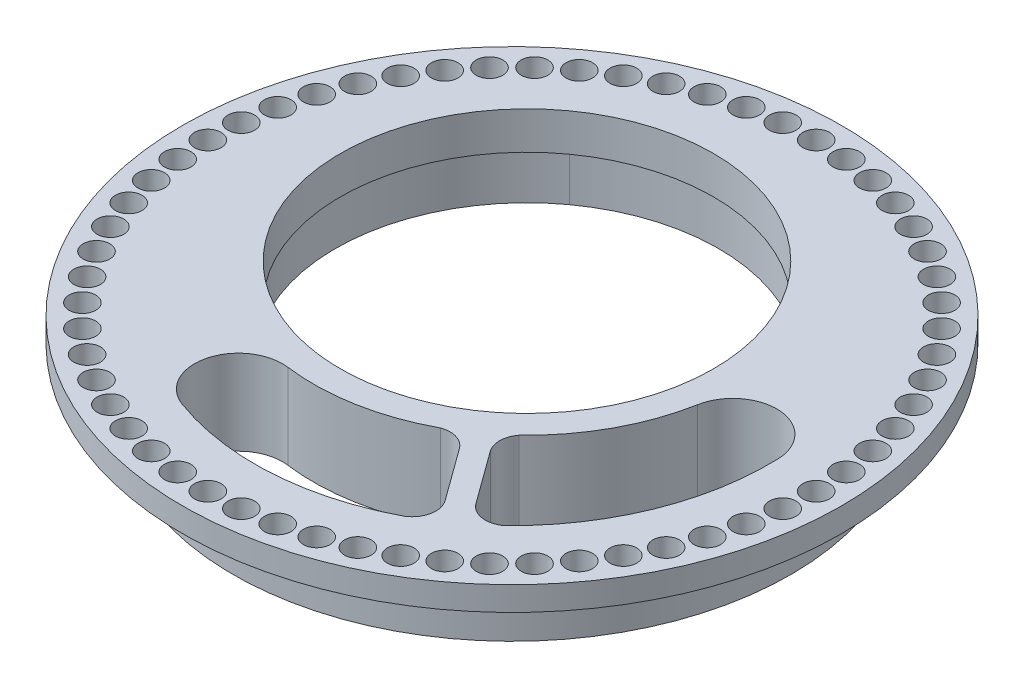
SolidWorks part; units mm, degrees
material "7075-T6, Plate (SS)"
ref_plane "X-Y Datum" through (0, 0, 0) normal (0, 0, 1) x (1, 0, 0)
ref_plane "X-Z Datum" through (0, 0, 0) normal (0, 1, 0) x (1, 0, 0)
ref_plane "Y-Z Datum" through (0, 0, 0) normal (1, 0, 0) x (0, 0, -1)
sketch "Sketch1" plane through (0, 0, 0) normal (0, 1, 0) x (1, 0, 0)
  line L0 (0, 0) -> (0, -12.7) construction
  line L1 (0, -43.0151) -> (0, 43.0151) construction
  line L2 (0, 61.9125) -> (0, 52.3875)
  circle A0 centre (0, -12.7) radius 35.052
  circle A1 centre (0, 0) radius 52.3875 construction
  circle A2 centre (0, 0) radius 57.15 construction
  circle A3 centre (0, 0) radius 61.9125
  point P12 (0, 57.15)
  dimension "D2" = 70.104
  dimension "D3" = 104.775
  dimension "D4" = 123.825
  dimension "D5" = 114.3
  dimension "D1" = 12.7
extrude "Boss-Extrude1" add sketch "Sketch1" along normal blind 4.5212
sketch "Sketch3" plane through (0, 4.5212, 0) normal (0, 1, 0) x (1, 0, 0)
  circle A0 centre (0, 0) radius 52.3875 construction
  circle A1 centre (0, 0) radius 52.3875
extrude "Boss-Extrude2" add sketch "Sketch3" along normal blind 11.43
sketch "Sketch4" plane through (0, 0, 0) normal (0, -1, 0) x (1, 0, 0)
  circle A0 centre (0, 12.7) radius 35.052 construction
  circle A1 centre (0, 12.7) radius 35.052
extrude "Cut-Extrude1" cut sketch "Sketch4" against normal through all
sketch "Sketch9" plane through (0, 15.9512, 0) normal (0, 1, 0) x (1, 0, 0)
  circle A0 centre (0, -12.7) radius 35.052 construction
  circle A1 centre (0, -12.7) radius 35.052 construction
  circle A2 centre (0, -12.7) radius 36
  dimension "D1" = 72
extrude "Cut-Extrude3" cut sketch "Sketch9" against normal blind 8.89
hole_wizard "Ø5.0mm Dowel Hole1" positions "Sketch7" profile "Sketch8" hole size "Ø5.0" standard "ANSI Metric" end condition through all
sketch "Sketch7" plane through (0, 4.5212, 0) normal (0, 1, 0) x (1, 0, 0)
  point P0 (0, 57.15)
sketch "Sketch8" plane through (0, 4.5212, -57.15) normal (1, 0, 0) x (0, 0, 1)
  line L0 (0, 0) -> (0, 4.5212)
  line L1 (0, 4.5212) -> (2.5, 4.5212)
  line L2 (2.5, 4.5212) -> (2.5, 0.025)
  line L3 (2.5, 0.025) -> (2.525, 0)
  line L5 (2.525, 0) -> (0, 0)
  line L6 (-2.5, 0.025) -> (-2.525, 0) construction
  line L11 (0, -6.35) -> (0, 107.95) construction
  dimension "Thru Hole Dia." = 5
  dimension "Thru Hole Depth" = 4.5212
  dimension "Near C'Sink Dia." = 5.05
  dimension "Near C'Sink Angle" = 90
pattern_circular "CirPattern1" count 60 over 360 about axis through (0, 0, 0) along (0, 1, 0) of "Ø5.0mm Dowel Hole1"
ref_point "Point1"
ref_plane "Plane1" through (0, 0, 0) normal (1, 0, 0) x (0, 0, -1)
split line "Split Line1"
ref_plane "Plane2" through (0, 7.9756, 0) normal (0, 1, 0) x (1, 0, 0)
sketch "Sketch14" plane through (0, 7.9756, 0) normal (0, 1, 0) x (1, 0, 0)
  circle A0 centre (-33.2491, 22.3603) radius 8.255
ref_point "Point4"
sketch "Sketch10" plane through (0, 15.9512, 0) normal (0, 1, 0) x (1, 0, 0)
  circle A0 centre (0, 0) radius 52.3875 construction
  circle A1 centre (0, 0) radius 52.3875 construction
  circle A3 centre (-33.2491, 22.3603) radius 8.255 construction
  circle A4 centre (33.2491, 22.3603) radius 8.255 construction
  arc A7 (0, -52.764) -> (0, 27.364) centre (0, -12.7) ccw
  arc A8 (0, 27.364) -> (0, -52.764) centre (0, -12.7) ccw
  arc A9 (0, -52.764) -> (0, 27.364) centre (0, -12.7) ccw construction
  arc A10 (0, 27.364) -> (0, -52.764) centre (0, -12.7) ccw construction
  circle A29 centre (0, 0) radius 48.3235 construction
  arc A30 (-27.5687, 16.3704) -> (27.5687, 16.3704) centre (0, -12.7) cw
  arc A31 (-40.0992, 26.967) -> (40.0992, 26.967) centre (0, 0) cw
  arc A32 (-40.0992, 26.967) -> (-27.5687, 16.3704) centre (-33.2491, 22.3603) ccw
  arc A33 (27.5687, 16.3704) -> (40.0992, 26.967) centre (33.2491, 22.3603) ccw
  dimension "D3" = 16.51
  dimension "D1" = 4.064
  dimension "D2" = 4.064
extrude "Cut-Extrude5" cut sketch "Sketch10" against normal through all contours A33 A31 A32 A30
sketch "Sketch15" plane through (0, 7.9756, 0) normal (0, 1, 0) x (1, 0, 0)
  line L1 (-2.1171, 31.2835) -> (-2.1171, 43.3958)
  line L4 (2.032, 31.291) -> (2.032, 43.4389)
  line L6 (-2.1764, 48.3235) -> (-2.1667, 48.2749) construction
  line L8 (2.1667, 48.2749) -> (2.1764, 48.3235) construction
  arc A0 (27.5687, 16.3704) -> (-27.5687, 16.3704) centre (0, -12.7) ccw construction
  arc A1 (27.5687, 16.3704) -> (-27.5687, 16.3704) centre (0, -12.7) ccw construction
  arc A2 (40.0992, 26.967) -> (-40.0992, 26.967) centre (0, 0) ccw construction
  arc A3 (-2.1171, 43.3958) -> (-6.9062, 47.8275) centre (-6.5621, 43.3958) ccw
  arc A4 (40.0992, 26.967) -> (-40.0992, 26.967) centre (0, 0) ccw construction
  arc A5 (6.5037, 47.8838) -> (2.032, 43.4389) centre (6.477, 43.4389) ccw
  arc A7 (-2.1171, 31.2835) -> (-5.362, 27.0036) centre (-6.5621, 31.2835) cw
  arc A9 (2.032, 31.291) -> (5.2509, 27.0184) centre (6.477, 31.291) ccw
  arc A10 (-6.9062, 47.8275) -> (6.5037, 47.8838) centre (0, 0) cw
  arc A11 (-5.362, 27.0036) -> (5.2509, 27.0184) centre (0, -12.7) cw
  point P9 (0, 37.4715)
  dimension "D1" = 4.445
  dimension "D2" = 2.1171
  dimension "D3" = 4.445
  dimension "D4" = 2.032
  dimension "D5" = 43.4389
  dimension "D6" = 31.2835
  dimension "D7" = 2.1171
  dimension "D8" = 12.148
  dimension "D9" = 12.1123
extrude "Boss-Extrude3" add sketch "Sketch15" along normal up to surface and the other way up to surface contours A9 L4 A5 A10 A3 L1 A7 A11 up to face at (0, 15.9512, -26.9504) other way up to face at (0, 0, -26.9504)
sketch "Sketch20" plane through (0, 4.5212, 0) normal (0, 1, 0) x (1, 0, 0)
  circle A0 centre (0, 0) radius 52.3875
  circle A2 centre (0, 0) radius 66.6087
sketch "Sketch25" plane through (0, 15.9512, 0) normal (0, 1, 0) x (1, 0, 0)
  line L6 (-4.6571, 31.2835) -> (-4.6571, 43.3958)
  line L7 (-4.6571, 31.2835) -> (-4.6571, 43.3958)
  line L12 (4.572, 43.4389) -> (4.572, 31.291)
  line L13 (4.572, 43.4389) -> (4.572, 31.291)
  circle A1 centre (-51.685, -7.6867) radius 0.134
  circle A2 centre (49.3335, -18.9489) radius 0.46
  arc A3 (48.8818, -18.8622) -> (48.9404, -18.71) centre (-0.2183, 0.1504) ccw
  arc A4 (48.8818, -18.8622) -> (48.9404, -18.71) centre (-0.2183, 0.1504) ccw
  arc A45 (-4.6571, 43.3958) -> (-6.6423, 45.2991) centre (-6.5621, 43.3958) ccw
  arc A46 (-5.9167, 29.4912) -> (-4.6571, 31.2835) centre (-6.5621, 31.2835) ccw
  arc A47 (-5.9167, 29.4912) -> (-29.3165, 18.2135) centre (0, -12.7) ccw
  arc A48 (-37.9914, 25.5495) -> (-29.3165, 18.2135) centre (-33.2491, 22.3603) ccw
  arc A49 (-6.6423, 45.2991) -> (-37.9914, 25.5495) centre (0, 0) ccw
  arc A50 (-4.6571, 43.3958) -> (-6.6423, 45.2991) centre (-6.5621, 43.3958) ccw
  arc A51 (-5.9167, 29.4912) -> (-4.6571, 31.2835) centre (-6.5621, 31.2835) ccw
  arc A52 (-5.9167, 29.4912) -> (-29.3165, 18.2135) centre (0, -12.7) ccw
  arc A53 (-37.9914, 25.5495) -> (-29.3165, 18.2135) centre (-33.2491, 22.3603) ccw
  arc A54 (-6.6423, 45.2991) -> (-37.9914, 25.5495) centre (0, 0) ccw
  circle A68 centre (-0.2183, 0.1504) radius 52.1224
  circle A69 centre (0, -12.7) radius 32.512
  circle A70 centre (0, -12.7) radius 32.512
  arc A72 (29.3165, 18.2135) -> (37.9914, 25.5495) centre (33.2491, 22.3603) ccw
  arc A73 (4.572, 31.291) -> (5.8124, 29.5056) centre (6.477, 31.291) ccw
  arc A74 (29.3165, 18.2135) -> (5.8124, 29.5056) centre (0, -12.7) ccw
  arc A75 (37.9914, 25.5495) -> (6.3564, 45.3401) centre (0, 0) ccw
  arc A76 (6.3564, 45.3401) -> (4.572, 43.4389) centre (6.477, 43.4389) ccw
  arc A77 (29.3165, 18.2135) -> (37.9914, 25.5495) centre (33.2491, 22.3603) ccw
  arc A78 (4.572, 31.291) -> (5.8124, 29.5056) centre (6.477, 31.291) ccw
  arc A79 (29.3165, 18.2135) -> (5.8124, 29.5056) centre (0, -12.7) ccw
  arc A80 (37.9914, 25.5495) -> (6.3564, 45.3401) centre (0, 0) ccw
  arc A81 (6.3564, 45.3401) -> (4.572, 43.4389) centre (6.477, 43.4389) ccw
  arc M3 (27.5687, 16.3704) -> (5.2509, 27.0184) centre (0, -12.7) ccw
  arc M4 (5.2509, 27.0184) -> (2.032, 31.291) centre (6.477, 31.291) cw
  line M5 (2.032, 31.291) -> (2.032, 43.4389)
  arc M6 (2.032, 43.4389) -> (6.5037, 47.8838) centre (6.477, 43.4389) cw
  arc M7 (6.5037, 47.8838) -> (40.0992, 26.967) centre (0, 0) cw
  arc M8 (40.0992, 26.967) -> (27.5687, 16.3704) centre (33.2491, 22.3603) cw
  arc M9 (-5.362, 27.0036) -> (-27.5687, 16.3704) centre (0, -12.7) ccw
  arc M10 (-27.5687, 16.3704) -> (-40.0992, 26.967) centre (-33.2491, 22.3603) cw
  arc M11 (-40.0992, 26.967) -> (-6.9062, 47.8275) centre (0, 0) cw
  arc M12 (-6.9062, 47.8275) -> (-2.1171, 43.3958) centre (-6.5621, 43.3958) cw
  line M13 (-2.1171, 43.3958) -> (-2.1171, 31.2835)
  arc M14 (-2.1171, 31.2835) -> (-5.362, 27.0036) centre (-6.5621, 31.2835) cw
  arc M15 (0, 23.3) -> (0, -48.7) centre (0, -12.7) cw
  arc M16 (0, -48.7) -> (0, 23.3) centre (0, -12.7) cw
  dimension "D1" = 2.54
  dimension "D2" = 2.54
  dimension "D3" = 2.54
extrude "Boss-Extrude5" [suppressed] add sketch "Sketch25" along normal blind 1.27 contours A54 A50 L7 A51 A52 A53 M9 M14 M13 M12 M11 M10 | A70 M15 M16 | A68 A1 M16 M15 M14 M9 M10 M11 M12 M13 M8 M3 M4 M5 M6 M7 | A81 A80 A77 A79 A78 L13 M3 M8 M7 M6 M5 M4
move or copy body "Body-Move/Copy1" bodies to move or copy 110 copy no rotation origin (0, 0, 0) rotation axis (0.9511, 0, -0.309) rotation angle 180
ref_point "Point5"
